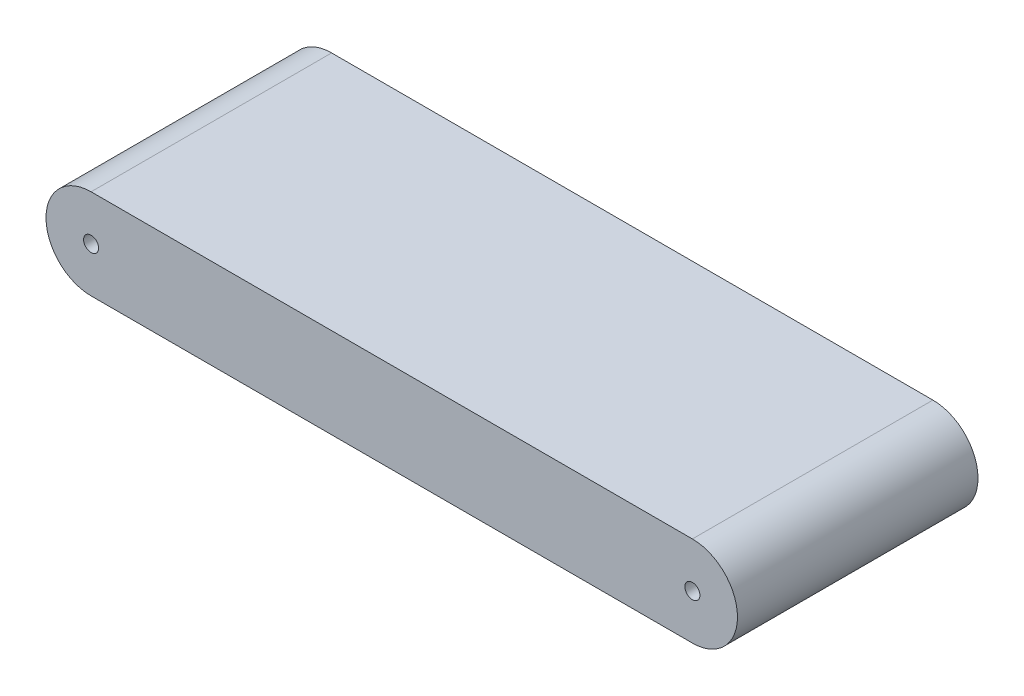
SolidWorks part; units mm, degrees
ref_plane "前视基准面" through (0, 0, 0) normal (0, 0, 1) x (1, 0, 0)
ref_plane "上视基准面" through (0, 0, 0) normal (0, 1, 0) x (1, 0, 0)
ref_plane "右视基准面" through (0, 0, 0) normal (1, 0, 0) x (0, 0, -1)
sketch "草图1" plane through (0, 0, 0) normal (0, 0, 1) x (1, 0, 0)
  line L0 (-100, 0) -> (100, 0) construction
  line L1 (-100, 15) -> (100, 15)
  line L2 (-100, -15) -> (100, -15)
  arc A0 (-100, 15) -> (-100, -15) centre (-100, 0) ccw
  arc A1 (100, -15) -> (100, 15) centre (100, 0) ccw
  point P2 (0, 0)
extrude "凸台-拉伸1" add sketch "草图1" along normal blind 80
sketch "草图2" plane through (0, 0, 80) normal (0, 0, 1) x (1, 0, 0)
  circle A0 centre (-100, 0) radius 2.5
  circle A1 centre (100, 0) radius 2.5
extrude "切除-拉伸1" cut sketch "草图2" against normal through all both and the other way through all
